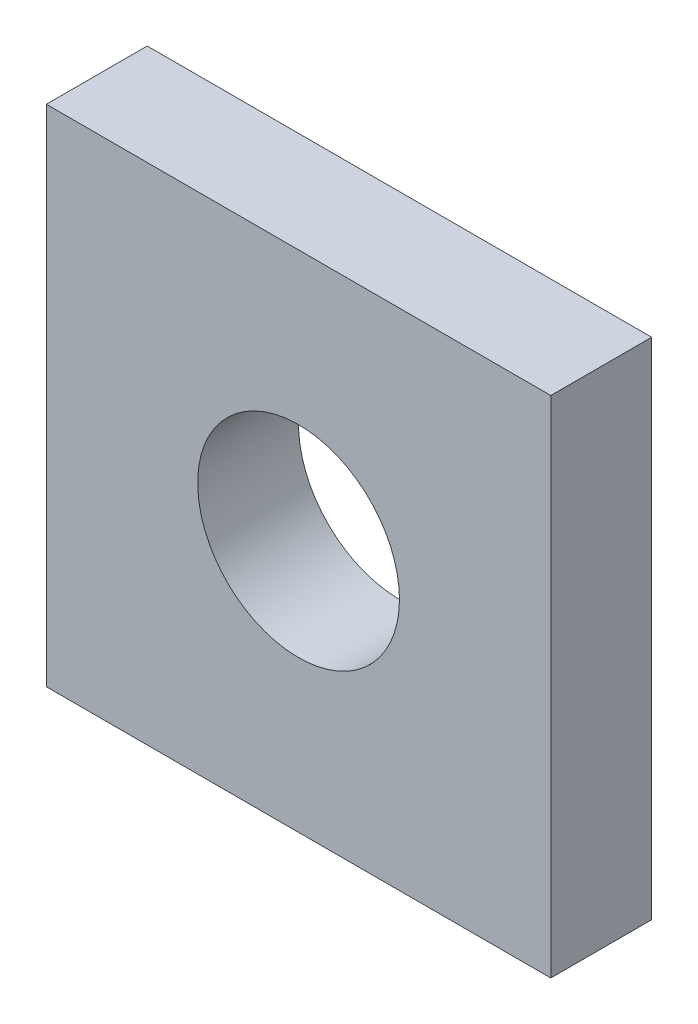
SolidWorks part; units mm, degrees
ref_plane "前视基准面" through (0, 0, 0) normal (0, 0, 1) x (1, 0, 0)
ref_plane "上视基准面" through (0, 0, 0) normal (0, 1, 0) x (1, 0, 0)
ref_plane "右视基准面" through (0, 0, 0) normal (1, 0, 0) x (0, 0, -1)
other "Configuration Table"
sketch "草图1" plane through (0, 0, 0) normal (0, 0, 1) x (1, 0, 0)
  line L1 (-250, -250) -> (250, -250)
  line L2 (-250, -250) -> (-250, 250)
  line L3 (-250, 250) -> (250, 250)
  line L4 (250, -250) -> (250, 250)
  line L5 (-250, -250) -> (250, 250) construction
  line L6 (-250, 250) -> (250, -250) construction
  point P0 (0, 0)
extrude "凸台-拉伸1" add sketch "草图1" along normal blind 100
sketch "草图2" plane through (0, 0, 0) normal (0, 0, 1) x (1, 0, 0)
  circle A0 centre (0, 0) radius 100
extrude "切除-拉伸1" cut sketch "草图2" along normal through all
